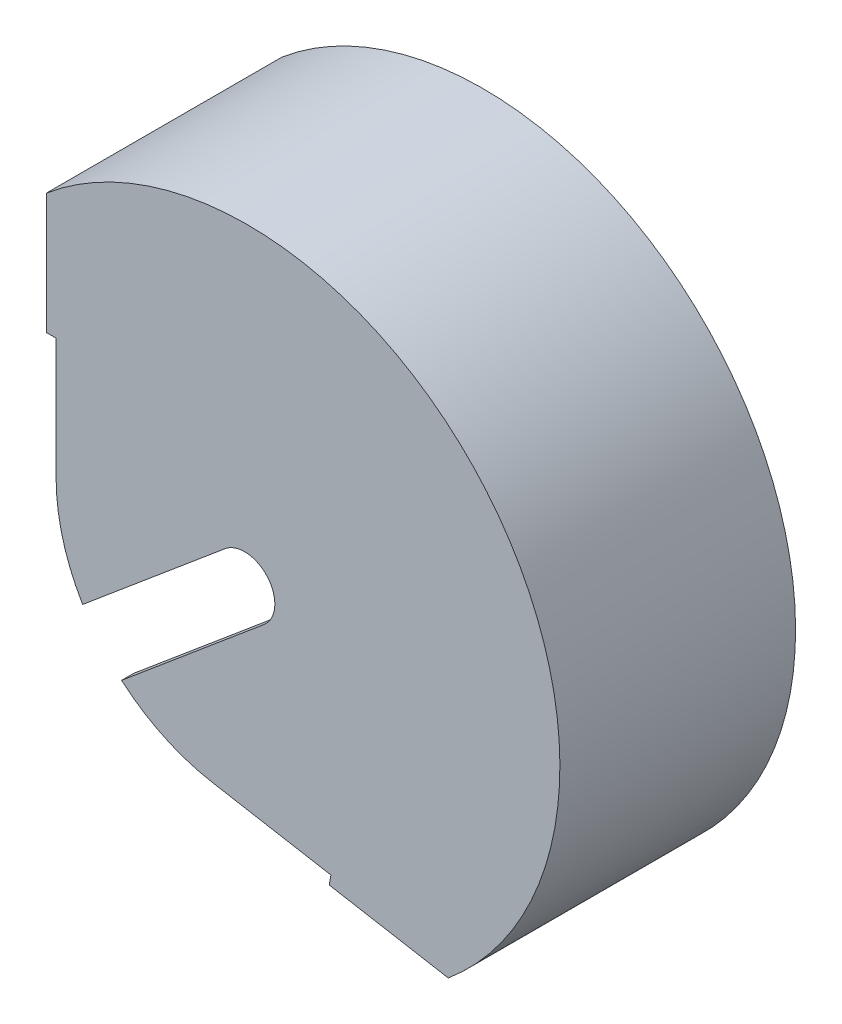
SolidWorks part; units mm, degrees
ref_plane "Front Plane" through (0, 0, 0) normal (0, 0, 1) x (1, 0, 0)
ref_plane "Top Plane" through (0, 0, 0) normal (0, 1, 0) x (1, 0, 0)
ref_plane "Right Plane" through (0, 0, 0) normal (1, 0, 0) x (0, 0, -1)
sketch "Sketch1" plane through (0, 0, 0) normal (0, 0, 1) x (1, 0, 0)
  line L0 (0, 0) -> (-39.624, 0)
  line L1 (0, 0) -> (-6.8806, -39.022)
  line L2 (-39.624, 0) -> (-39.624, 25.4)
  line L3 (-6.8806, -39.022) -> (18.1335, -43.4327)
  line L4 (-39.624, 25.4) -> (-41.656, 25.4)
  line L5 (18.1335, -43.4327) -> (17.7806, -45.4338)
  line L6 (-41.656, 25.4) -> (-41.656, 50.8)
  line L7 (17.7806, -45.4338) -> (42.7947, -49.8445)
  arc A0 (-39.624, 0) -> (-6.8806, -39.022) centre (0, 0) ccw
  arc A1 (42.7947, -49.8445) -> (-41.656, 50.8) centre (0.5694, 0.4778) ccw
  dimension "D1" = 79.248
  dimension "D2" = 80
  dimension "D3" = 25.4
  dimension "D4" = 25.4
  dimension "D5" = 2.032
  dimension "D6" = 2.032
  dimension "D7" = 25.4
extrude "Side" add sketch "Sketch1" along normal blind 2.54 contours L7 A1 L6 L4 L2 L0 L1 L3 L5 | L0 A0 L1
sketch "Sketch2" plane through (0, 0, 2.54) normal (0, 0, 1) x (1, 0, 0)
  line L0 (-40.0233, 48.8542) -> (-41.656, 48.8542)
  line L2 (41.1621, -47.8987) -> (40.8786, -49.5066)
  line L4 (-41.656, 25.4) -> (-41.656, 50.8) construction
  line L5 (17.7806, -45.4338) -> (42.7947, -49.8445) construction
  line L6 (-41.656, 48.8542) -> (-41.656, 50.8)
  line L7 (40.8786, -49.5066) -> (42.7947, -49.8445)
  arc A2 (41.1621, -47.8987) -> (-40.0233, 48.8542) centre (0.5694, 0.4778) ccw
  arc A3 (41.1621, -47.8987) -> (-40.0233, 48.8542) centre (0.5694, 0.4778) ccw
  arc A5 (42.7947, -49.8445) -> (-41.656, 50.8) centre (0.5694, 0.4778) ccw
  arc A6 (42.7947, -49.8445) -> (-41.656, 50.8) centre (0.5694, 0.4778) ccw
  line M6 (18.1335, -43.4327) -> (17.7806, -45.4338)
  line M7 (17.7806, -45.4338) -> (42.7947, -49.8445)
  arc M8 (42.7947, -49.8445) -> (-41.656, 50.8) centre (0.5694, 0.4778) ccw
  line M9 (-41.656, 50.8) -> (-41.656, 25.4)
  line M10 (-41.656, 25.4) -> (-39.624, 25.4)
  dimension "D1" = 2.54
  dimension "D2" = 0
extrude "Cover" add sketch "Sketch2" along normal blind 44.45 contours A3 L2 L0 M6 M7 M8 M9 M10
ref_plane "midplane" through (0, 0, 24.765) normal (0, 0, 1) x (1, 0, 0)
mirror "Mirror1" about plane through (0, 0, 24.765) normal (0, 0, 1) of "Side"
sketch "Sketch3" plane through (0, 0, 49.53) normal (0, 0, 1) x (1, 0, 0)
  line L0 (0, 0) -> (-30.3537, -25.4698) construction
  line L1 (-4.0817, 4.8644) -> (-37.1595, -22.8912)
  line L2 (-37.1595, -22.8912) -> (-28.9961, -32.62)
  line L3 (-28.9961, -32.62) -> (4.0817, -4.8644)
  arc A0 (4.0817, -4.8644) -> (-4.0817, 4.8644) centre (0, 0) ccw
  arc A1 (-39.624, 0) -> (-6.8806, -39.022) centre (0, 0) ccw construction
  dimension "D2" = 12.7
  dimension "D1" = 43.18
extrude "Flywheel slit" cut sketch "Sketch3" against normal up to next
sketch "Sketch4" plane through (0, 0, 0) normal (0, 0, -1) x (-1, 0, 0)
  line L0 (0, 0) -> (39.624, 0) construction
  line L1 (0, 0) -> (33.2775, 10.174) construction
  line L2 (-2.1162, -33.5317) -> (33.2775, 10.174) construction
  line L3 (33.2775, 10.174) -> (3.2382, -36.9452) construction
  line L4 (3.2382, -36.9452) -> (-2.1162, -33.5317) construction
  circle A2 centre (-2.1162, -33.5317) radius 3.2639
  circle A3 centre (33.2775, 10.174) radius 3.2639
  dimension "D1" = 6.35
  dimension "D2" = 55.88
  dimension "D4" = 6.5278
  dimension "D5" = 17
extrude "Mount holes" cut sketch "Sketch4" against normal up to next
sketch "Sketch5" plane through (0, 0, 0) normal (0, 0, -1) x (-1, 0, 0)
  circle A0 centre (0, 0) radius 3.81
  arc A1 (4.0817, 4.8644) -> (-4.0817, -4.8644) centre (0, 0) ccw construction
  dimension "D1" = 7.62
extrude "Axle Holder Hole" cut sketch "Sketch5" against normal up to next
